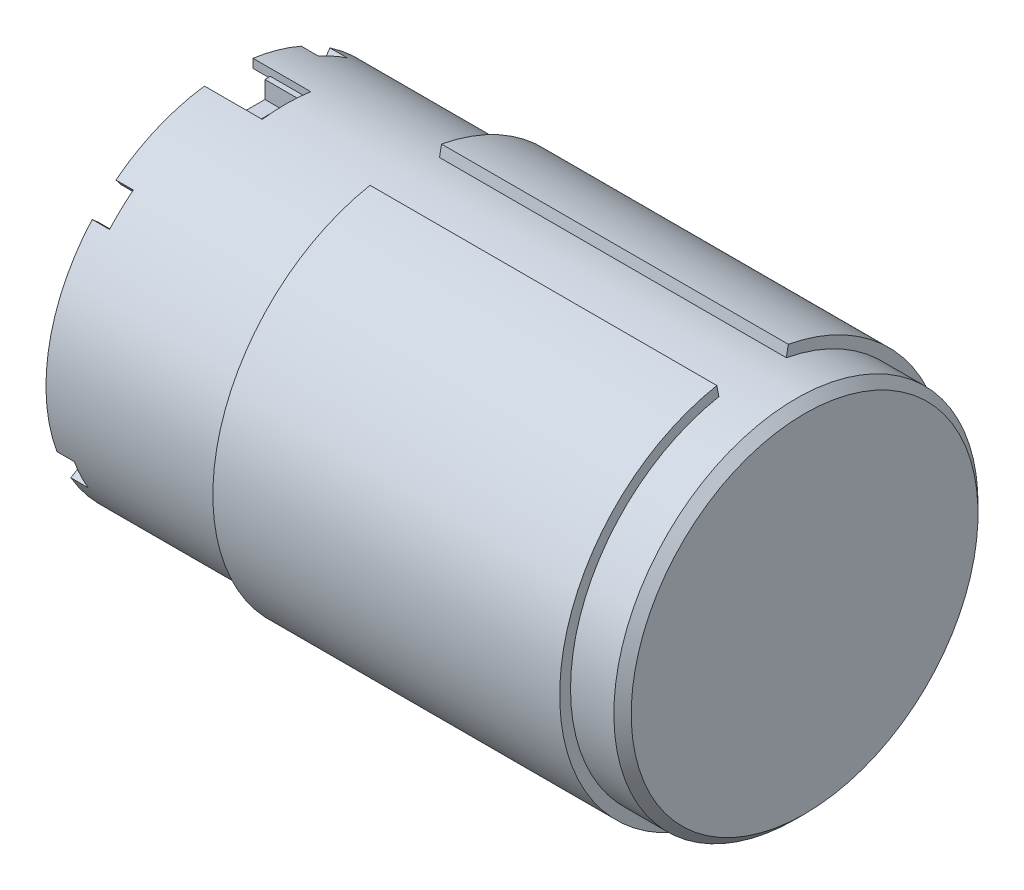
SolidWorks part; units mm, degrees
ref_plane "Front Plane" through (0, 0, 0) normal (0, 0, 1) x (1, 0, 0)
ref_plane "Top Plane" through (0, 0, 0) normal (0, 1, 0) x (1, 0, 0)
ref_plane "Right Plane" through (0, 0, 0) normal (1, 0, 0) x (0, 0, -1)
sketch "Sketch1" plane through (0, 0, 0) normal (0, 0, 1) x (1, 0, 0)
  line L0 (0, 100.0906) -> (0, -100.0906) construction
  line L1 (169.0695, 0) -> (-169.0695, 0) construction
  line L2 (43.3319, 0) -> (43.3319, -21)
  line L3 (43.3319, -21) -> (63.8319, -21)
  line L4 (109.8319, -21) -> (109.8319, 0)
  line L5 (109.8319, -21) -> (103.8319, -21)
  line L6 (103.8319, -21) -> (103.8319, -22.25)
  line L7 (103.8319, -22.25) -> (63.8319, -22.25)
  line L8 (63.8319, -22.25) -> (63.8319, -21)
  line L9 (103.8319, -21) -> (109.8319, -21)
  line L10 (43.3319, 0) -> (109.8319, 0)
  point P4 (0, 0)
  point P8 (0, 0)
revolve "Revolve1" add sketch "Sketch1" angle 360 about L1
chamfer "Chamfer2" distance 1 angle 45 1 edges at (109.8319, 21, 0)
sketch "Sketch2" plane through (103.8319, 0, 0) normal (1, 0, 0) x (0, 0, -1)
  line L0 (-3.8887, 20.6368) -> (-4.1201, 21.8652)
  line L1 (3.8887, 20.6368) -> (4.1201, 21.8652)
  line L2 (-8.6292, 0) -> (11.2492, 0) construction
  line L3 (3.8887, -20.6368) -> (4.1201, -21.8652)
  line L4 (-3.8887, -20.6368) -> (-4.1201, -21.8652)
  circle A0 centre (0, 0) radius 22.25
  circle A1 centre (0, 0) radius 21
  circle M3 centre (0, 0) radius 22.25
  circle M4 centre (0, 0) radius 21
extrude "Cut-Extrude1" cut sketch "Sketch2" against normal blind 111 contours L1 L0 M4 M3 | L4 L3 M4 M3
ref_plane "Plane2" through (0, 21, 0) normal (0, 1, 0) x (1, 0, 0)
sketch "Sketch3" plane through (0, 21, 0) normal (0, 1, 0) x (1, 0, 0)
  line L0 (43.3319, 2.8766) -> (49.9917, 2.8766)
  line L1 (43.3319, 21) -> (43.3319, -21) construction
  line L2 (49.9917, 2.8766) -> (49.9917, -2.7155)
  line L3 (49.9917, -2.7155) -> (43.3319, -2.7155)
  line L4 (43.3319, -2.7155) -> (43.3319, 2.8766)
extrude "Cut-Extrude2" cut sketch "Sketch3" against normal blind 1
sketch "Sketch4" plane through (0, 20, 0) normal (0, 1, 0) x (1, 0, 0)
  line L0 (43.3319, 2.2553) -> (49.069, 2.2553)
  line L1 (43.3319, 2.8766) -> (43.3319, -2.7155) construction
  line L2 (49.069, 2.2553) -> (49.069, -2.1446)
  line L3 (49.069, -2.1446) -> (43.3319, -2.1446)
  line L4 (43.3319, -2.1446) -> (43.3319, 2.2553)
extrude "Cut-Extrude3" cut sketch "Sketch4" against normal blind 2
sketch "Sketch5" plane through (43.3319, 0, 0) normal (-1, 0, 0) x (0, 0, 1)
  line L0 (12.3138, 15.7598) -> (12.9294, 16.5478)
  line L1 (14.9251, 13.3132) -> (15.6713, 13.9789)
  line L2 (18.7936, -6.841) -> (19.7333, -7.1831)
  line L3 (17.2737, -10.0806) -> (18.1374, -10.5846)
  line L4 (-0.6987, -19.9878) -> (-0.7336, -20.9872)
  line L5 (-4.2493, -19.5434) -> (-4.4618, -20.5205)
  line L6 (-19.2254, -5.5121) -> (-20.1867, -5.7877)
  line L7 (-19.9, -1.9979) -> (-20.895, -2.0978)
  line L8 (-11.1833, 16.5811) -> (-11.7425, 17.4102)
  line L9 (-8.0495, 18.3086) -> (-8.452, 19.224)
  circle A0 centre (0, 0) radius 21
  circle A1 centre (0, 0) radius 20
  point P27 (0, 0)
  line M3 (2.1446, 18) -> (-2.2553, 18)
  line M4 (-2.2553, 18) -> (-2.2553, 20)
  arc M7 (-2.8766, 20.8021) -> (2.7155, 20.8237) centre (0, 0) ccw
  line M10 (2.1446, 20) -> (2.1446, 18)
  dimension "D1" = 5
extrude "Cut-Extrude4" cut sketch "Sketch5" against normal blind 2 contours A1 M10 M3 M4 | A1 L9 L8 M7 | A1 L1 L0 M7 | A1 L3 L2 M7 | A1 L5 L4 M7 | A1 L7 L6 M7
sketch "Sketch6" plane through (43.3319, 0, 0) normal (-1, 0, 0) x (0, 0, 1)
  line L0 (2.7155, 20.8237) -> (2.7155, 19.8148)
  line L1 (2.7155, 19.8148) -> (2.1446, 19.8148)
  line L2 (2.1446, 18) -> (2.1446, 20) construction
  line L3 (2.1446, 19.8148) -> (2.1446, 20.8237)
  line L4 (2.1446, 20.8237) -> (2.7155, 20.8237)
  line L5 (-2.8766, 20.8021) -> (-2.8766, 19.7206)
  line L6 (-2.8766, 19.7206) -> (-2.2553, 19.7206)
  line L7 (-2.2553, 18) -> (-2.2553, 19.8724) construction
  line L8 (-2.2553, 19.7206) -> (-2.2553, 20.9082)
  line L9 (-2.2553, 20.9082) -> (-2.8766, 20.9082)
  line L10 (-2.8766, 20.9082) -> (-2.8766, 20.8021)
  arc A0 (12.3138, 15.7598) -> (2.1446, 19.8847) centre (0, 0) ccw construction
extrude "Cut-Extrude5" cut sketch "Sketch6" against normal blind 2
